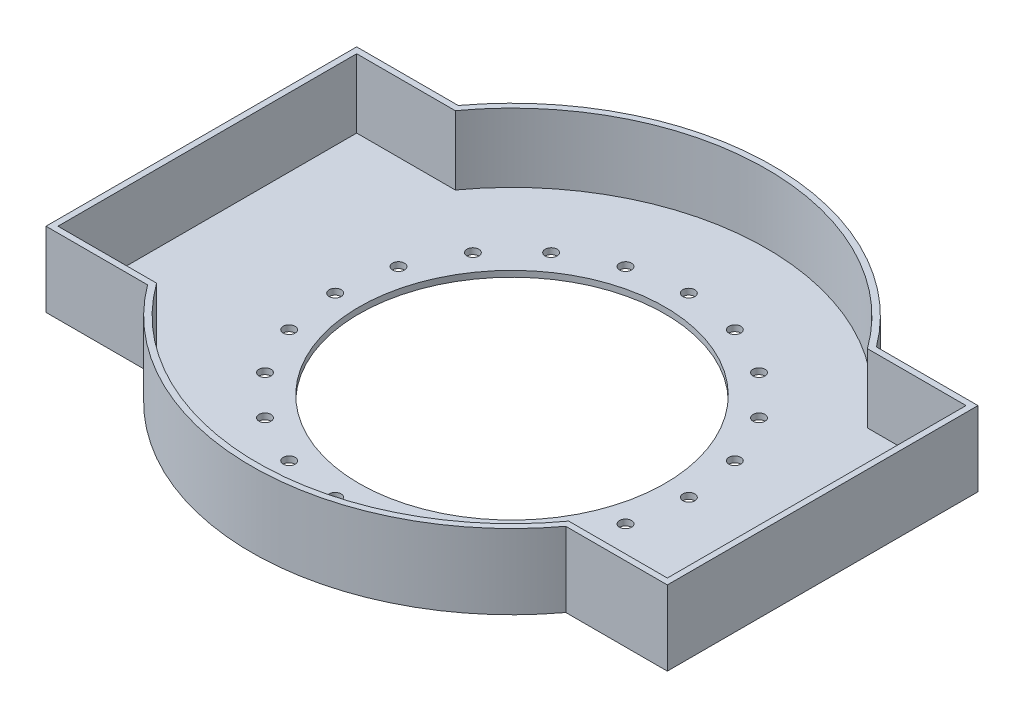
SolidWorks part; units mm, degrees
ref_plane "Plan de face" through (0, 0, 0) normal (0, 0, 1) x (1, 0, 0)
ref_plane "Plan de dessus" through (0, 0, 0) normal (0, 1, 0) x (1, 0, 0)
ref_plane "Plan de droite" through (0, 0, 0) normal (1, 0, 0) x (0, 0, -1)
sketch "Esquisse1" plane through (0, 0, 0) normal (0, 0, 1) x (1, 0, 0)
  line L0 (-256, 27.4194) -> (-256, -16.0215) construction
  line L1 (0, 0) -> (80, 0)
  line L2 (0, 0) -> (0, 90)
  line L3 (0, 90) -> (80, 90)
  line L4 (80, 0) -> (80, 52.5)
  line L5 (80, 72.5) -> (80, 90)
  arc A0 (80, 72.5) -> (80, 52.5) centre (80, 62.5) ccw
  dimension "D4" = 10
  dimension "D1" = 80
  dimension "D2" = 90
  dimension "D3" = 62.5
  dimension "D5" = 256
revolve "Révolution1" add sketch "Esquisse1" angle 360 about L0
sketch "Esquisse2" plane through (0, 0, 0) normal (0, -1, 0) x (1, 0, 0)
  line L0 (0, 0) -> (35.0097, 0) construction
  line L1 (0, 0) -> (80, 0) construction
  circle A0 centre (-256, 0) radius 336 construction
  circle A1 centre (40, 0) radius 10
  dimension "D2" = 20
  dimension "D1" = 40
extrude "Enlèv. mat.-Extru.1" cut sketch "Esquisse2" against normal through all
pattern_circular "Répétition circulaire1" count 20 over 360 about axis through (-256, 0, 0) along (0, 1, 0) of "Enlèv. mat.-Extru.1"
sketch "Esquisse5" plane through (0, 0, 0) normal (0, -1, 0) x (1, 0, 0)
  circle A1 centre (-256, 0) radius 336 construction
  circle A2 centre (-256, 0) radius 436
  circle A3 centre (-256, 0) radius 436
  circle A4 centre (-256, 0) radius 336
  dimension "D1" = 100
extrude "Boss.-Extru.1" add sketch "Esquisse5" against normal blind 10
sketch "Esquisse6" plane through (0, 10, 0) normal (0, 1, 0) x (1, 0, 0)
  circle A1 centre (-256, 0) radius 436 construction
  circle A2 centre (-256, 0) radius 426
  circle A3 centre (-256, 0) radius 426
  circle A4 centre (-256, 0) radius 436
  dimension "D1" = 10
extrude "Boss.-Extru.2" add sketch "Esquisse6" along normal blind 115
sketch "Esquisse7" plane through (0, 0, 0) normal (0, -1, 0) x (1, 0, 0)
  line L1 (93.9943, 260) -> (263.9943, 260)
  line L3 (93.9943, -260) -> (263.9943, -260)
  line L4 (263.9943, 260) -> (263.9943, -260)
  circle A0 centre (-256, 0) radius 436 construction
  arc A1 (93.9943, -260) -> (93.9943, 260) centre (-256, 0) ccw
  dimension "D1" = 520
  dimension "D2" = 170
extrude "Boss.-Extru.3" add sketch "Esquisse7" against normal blind 10
sketch "Esquisse8" plane through (0, 10, 0) normal (0, 1, 0) x (1, 0, 0)
  line L3 (253.9943, 250) -> (101.2058, 250)
  line L4 (253.9943, -250) -> (101.2058, -250)
  line L5 (113.3454, 250) -> (101.2058, 250)
  line L6 (113.3454, -250) -> (253.9943, -250)
  line L7 (253.9943, -250) -> (253.9943, 250)
  line L8 (253.9943, 250) -> (113.3454, 250)
  line L9 (113.3454, -250) -> (253.9943, -250)
  line L10 (253.9943, -250) -> (253.9943, 250)
  line L11 (253.9943, 250) -> (113.3454, 250)
  line L12 (113.3454, -250) -> (101.2058, -250)
  line L13 (263.9943, -260) -> (93.9943, -260) construction
  line L14 (263.9943, 260) -> (263.9943, -260) construction
  line L15 (93.9943, 260) -> (263.9943, 260) construction
  line L16 (263.9943, -260) -> (93.9943, -260)
  line L17 (263.9943, 260) -> (263.9943, -260)
  line L18 (93.9943, 260) -> (263.9943, 260)
  arc A1 (93.9943, -260) -> (93.9943, 260) centre (-256, 0) ccw construction
  arc A2 (113.3454, -250) -> (113.3454, 250) centre (-256, 0) ccw
  arc A4 (101.2058, 250) -> (93.9943, 260) centre (-256, 0) ccw
  arc A5 (93.9943, -260) -> (101.2058, -250) centre (-256, 0) ccw
  arc M9 (93.9943, 260) -> (93.9943, -260) centre (-256, 0) cw
  line M10 (93.9943, -260) -> (263.9943, -260)
  line M11 (263.9943, -260) -> (263.9943, 260)
  line M12 (263.9943, 260) -> (93.9943, 260)
  dimension "D1" = 10
extrude "Boss.-Extru.4" add sketch "Esquisse8" along normal blind 115 contours L10 L4 L3 M9 M10 M11 M12
sketch "Esquisse9" plane through (0, 125, 0) normal (0, 1, 0) x (1, 0, 0)
  line L0 (101.2058, -250) -> (88.929, -250)
  line L1 (101.2058, 250) -> (88.929, 250)
  line L5 (101.2058, -250) -> (253.9943, -250)
  line L6 (253.9943, 250) -> (101.2058, 250)
  line L7 (253.9943, -250) -> (253.9943, 250)
  circle A0 centre (-256, 0) radius 426 construction
  circle A1 centre (-256, 0) radius 426 construction
  arc A2 (88.929, -250) -> (88.929, 250) centre (-256, 0) ccw
  arc A3 (101.2058, -250) -> (101.2058, 250) centre (-256, 0) ccw
  arc A4 (101.2058, -250) -> (101.2058, 250) centre (-256, 0) ccw
  dimension "D1" = 0
extrude "Enlèv. mat.-Extru.3" cut sketch "Esquisse9" against normal blind 115
pattern_circular "Répétition circulaire6" count 2 over 360 of "Enlèv. mat.-Extru.3", "Boss.-Extru.4", "Boss.-Extru.3"
sketch "Esquisse10" plane through (0, 90, 0) normal (0, 1, 0) x (1, 0, 0)
  circle A1 centre (-256, 0) radius 336
  circle A2 centre (-256, 0) radius 336
  dimension "D1" = 0
extrude "Enlèv. mat.-Extru.4" cut sketch "Esquisse10" against normal blind 80 contours A2
